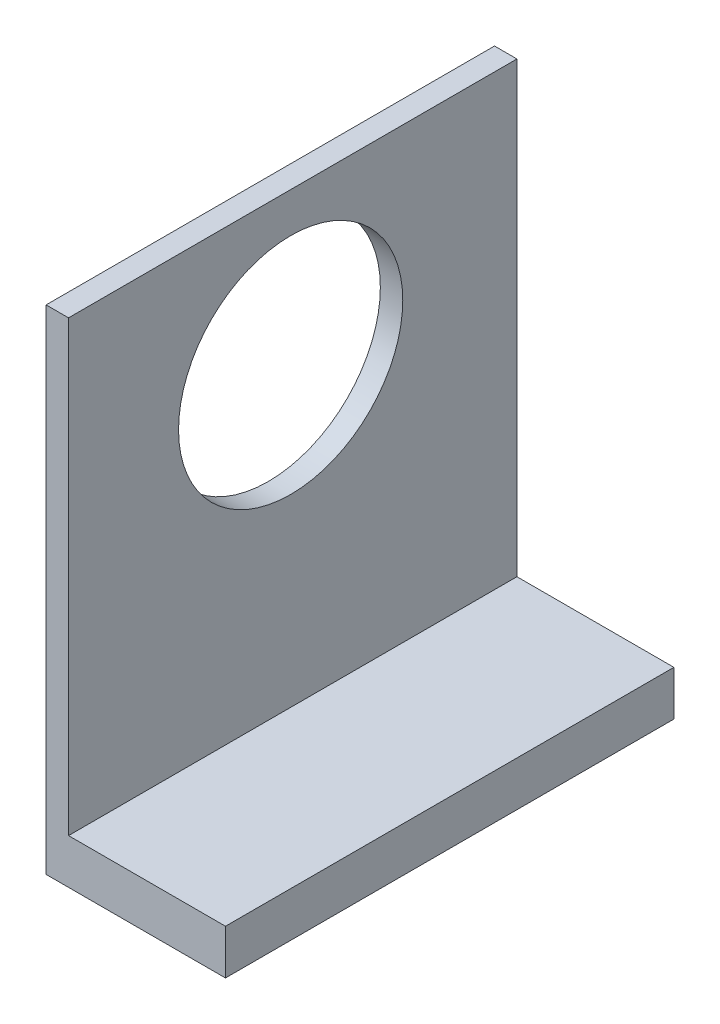
SolidWorks part; units mm, degrees
ref_plane "Front Plane" through (0, 0, 0) normal (0, 0, 1) x (1, 0, 0)
ref_plane "Top Plane" through (0, 0, 0) normal (0, 1, 0) x (1, 0, 0)
ref_plane "Right Plane" through (0, 0, 0) normal (1, 0, 0) x (0, 0, -1)
sketch "Sketch1" plane through (0, 0, 0) normal (0, 0, 1) x (1, 0, 0)
  line L0 (0, 0) -> (8, 0)
  line L1 (8, 0) -> (8, 2)
  line L2 (8, 2) -> (1, 2)
  line L3 (1, 2) -> (1, 22)
  line L4 (1, 22) -> (0, 22)
  line L5 (0, 0) -> (0, 22)
  dimension "D1" = 22
  dimension "D2" = 1
  dimension "D3" = 7
  dimension "D4" = 2
  dimension "D5" = 8
extrude "Boss-Extrude1" add sketch "Sketch1" along normal blind 20
sketch "Sketch2" plane through (1, 0, 0) normal (1, 0, 0) x (0, 0, -1)
  circle A0 centre (-10.093, 15.2224) radius 5
extrude "Cut-Extrude1" cut sketch "Sketch2" against normal blind 10
